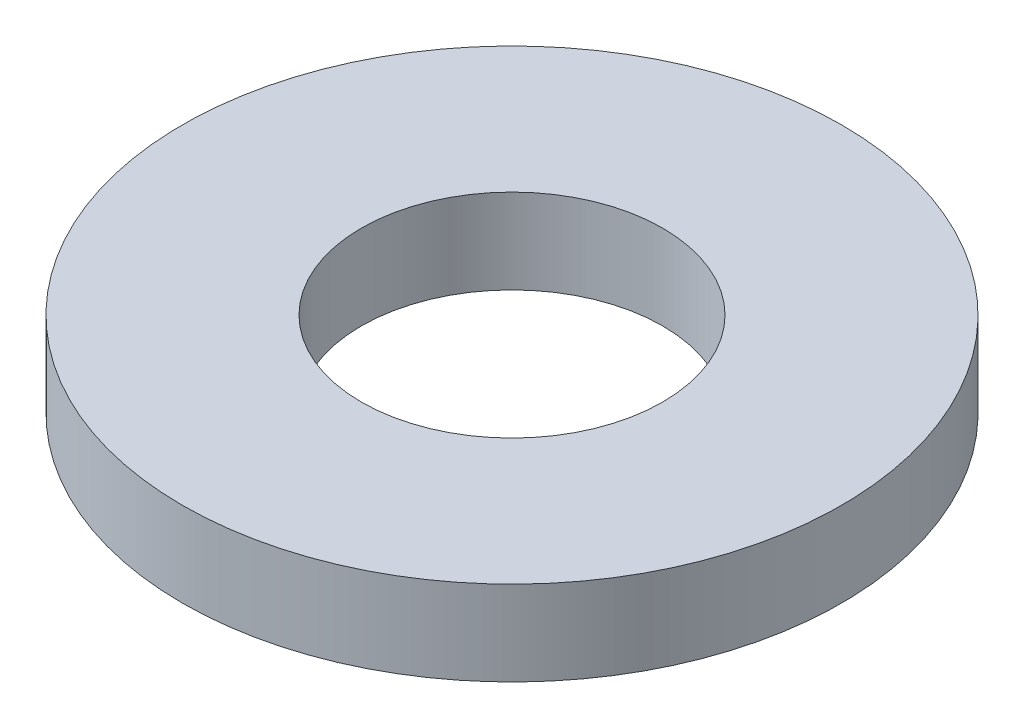
SolidWorks part; units mm, degrees
ref_plane "Front Plane" through (0, 0, 0) normal (0, 0, 1) x (1, 0, 0)
ref_plane "Top Plane" through (0, 0, 0) normal (0, 1, 0) x (1, 0, 0)
ref_plane "Right Plane" through (0, 0, 0) normal (1, 0, 0) x (0, 0, -1)
sketch "Эскиз1" plane through (0, 0, 0) normal (0, 1, 0) x (1, 0, 0)
  circle A0 centre (0, 0) radius 3.5
  circle A1 centre (0, 0) radius 1.6
  dimension "D1" = 3.2
  dimension "D2" = 7
extrude "Вытянуть1" add sketch "Эскиз1" along normal blind 0.9
